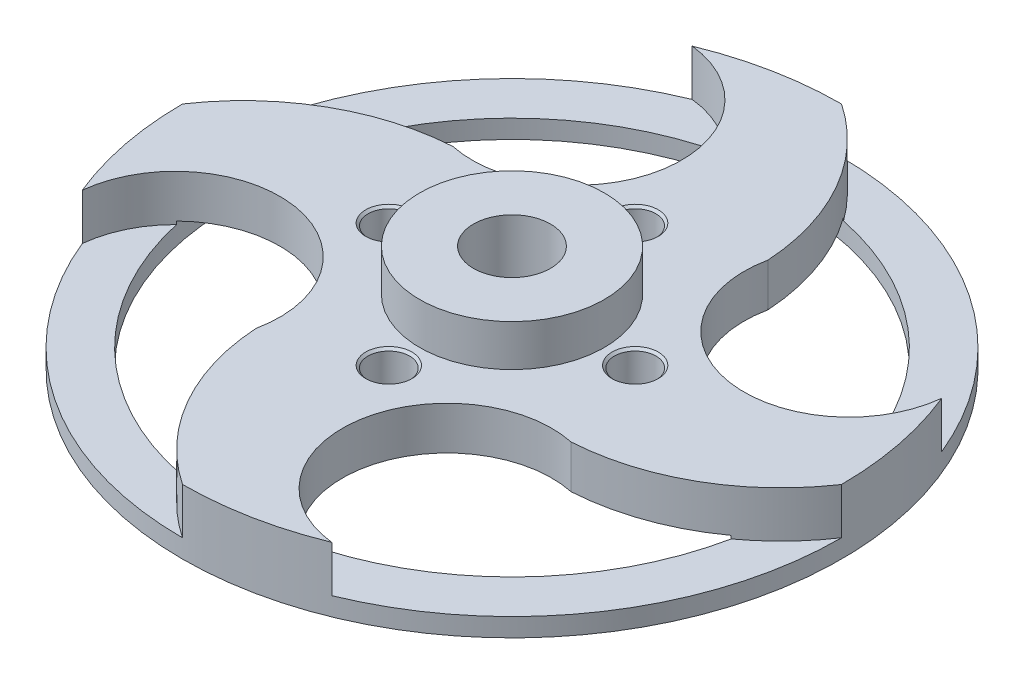
SolidWorks part; units mm, degrees
ref_plane "前视基准面" through (0, 0, 0) normal (0, 0, 1) x (1, 0, 0)
ref_plane "上视基准面" through (0, 0, 0) normal (0, 1, 0) x (1, 0, 0)
ref_plane "右视基准面" through (0, 0, 0) normal (1, 0, 0) x (0, 0, -1)
sketch "草图4" plane through (0, 0, 0) normal (0, 1, 0) x (1, 0, 0)
  circle A0 centre (0, 0) radius 21.4
  dimension "D1" = 42.8
extrude "凸台-拉伸2" add sketch "草图4" along normal blind 1.2 contours A0
sketch "草图5" plane through (0, 0, 0) normal (0, 1, 0) x (1, 0, 0)
  line L0 (0, 21.4) -> (0, -23.9544) construction
  line L1 (21.4, 0) -> (-30.224, 0) construction
  arc A0 (0, 21.4) -> (-8.1028, 19.8067) centre (0, 0) ccw
  circle A1 centre (0, 0) radius 21.4 construction
  circle A2 centre (0, 0) radius 7.3 construction
  arc A3 (-21.4, 0) -> (-19.8067, -8.1028) centre (0, 0) ccw
  arc A4 (0, -21.4) -> (8.1028, -19.8067) centre (0, 0) ccw
  arc A5 (21.4, 0) -> (19.8067, 8.1028) centre (0, 0) ccw
  arc A7 (-10.2294, 6.3912) -> (-8.1028, 19.8067) centre (-8.8299, 13.0457) ccw
  arc A9 (6.3912, 10.2294) -> (0, 21.4) centre (-8.1046, 9.3494) ccw
  arc A10 (6.3912, 10.2294) -> (19.8067, 8.1028) centre (13.0457, 8.8299) ccw
  arc A11 (10.2294, -6.3912) -> (21.4, 0) centre (9.3494, 8.1046) ccw
  arc A12 (10.2294, -6.3912) -> (8.1028, -19.8067) centre (8.8299, -13.0457) ccw
  arc A13 (-6.3912, -10.2294) -> (0, -21.4) centre (8.1046, -9.3494) ccw
  arc A14 (-6.3912, -10.2294) -> (-19.8067, -8.1028) centre (-13.0457, -8.8299) ccw
  arc A15 (-10.2294, 6.3912) -> (-21.4, 0) centre (-9.3494, -8.1046) ccw
  point P22 (0, 0)
  point P48 (0, 0)
  dimension "D3" = 14.6
  dimension "D4" = 6.8
  dimension "D7" = 4
extrude "凸台-拉伸5" add sketch "草图5" along normal blind 4.2 contours A7 A0 A9 A10 A5 A11 A12 A4 A13 A14 A3 A15
sketch "草图7" plane through (0, 0, 0) normal (0, -1, 0) x (1, 0, 0)
  circle A0 centre (0, 0) radius 18.25
  dimension "D1" = 36.5
extrude "切除-拉伸2" cut sketch "草图7" against normal blind 1.4 contours A0
sketch "草图9" plane through (0, 4.2, 0) normal (0, 1, 0) x (1, 0, 0)
  circle A0 centre (0, 0) radius 6
  dimension "D1" = 12
extrude "凸台-拉伸6" add sketch "草图9" along normal blind 2.7 contours A0
sketch "草图10" plane through (0, 6.9, 0) normal (0, 1, 0) x (1, 0, 0)
  circle A0 centre (0, 0) radius 2.5
  dimension "D1" = 5
extrude "切除-拉伸3" cut sketch "草图10" against normal through all
sketch "草图11" plane through (0, 4.2, 0) normal (0, 1, 0) x (1, 0, 0)
  circle A0 centre (0, 0) radius 8 construction
  circle A1 centre (0, 8) radius 1.5
  circle A2 centre (8, 0) radius 1.5
  circle A3 centre (0, -8) radius 1.5
  circle A4 centre (-8, 0) radius 1.5
  point P14 (0, 0)
  dimension "D1" = 16
  dimension "D2" = 3
  dimension "D3" = 4
hole_wizard "打孔尺寸(%根据)内六角花形半沉头螺钉的类型1" positions "3D草图2" profile "草图13" countersink size "M6" standard "GB" end condition through all
sketch3d "3D草图2"
  point P0 (-8, 4.2, 0)
  point P3 (0, 4.2, -8)
  point P6 (8, 4.2, 0)
  point P9 (0, 4.2, 8)
sketch "草图13" plane through (-8, 4.2, 0) normal (1, 0, 0) x (0, 0, 1)
  line L0 (0, 0) -> (0, 4.2)
  line L1 (0, 4.2) -> (1.35, 4.2)
  line L2 (1.35, 4.2) -> (1.35, 0.15)
  line L3 (1.35, 0.15) -> (1.5, 0)
  line L5 (1.5, 0) -> (0, 0)
  line L6 (-1.35, 0.15) -> (-1.5, 0) construction
  line L11 (0, -6.35) -> (0, 107.95) construction
  dimension "通孔孔直径" = 2.7
  dimension "通孔孔深度" = 4.2
  dimension "近端锥形沉头孔直径" = 3
  dimension "近端锥形沉头孔角度" = 90
